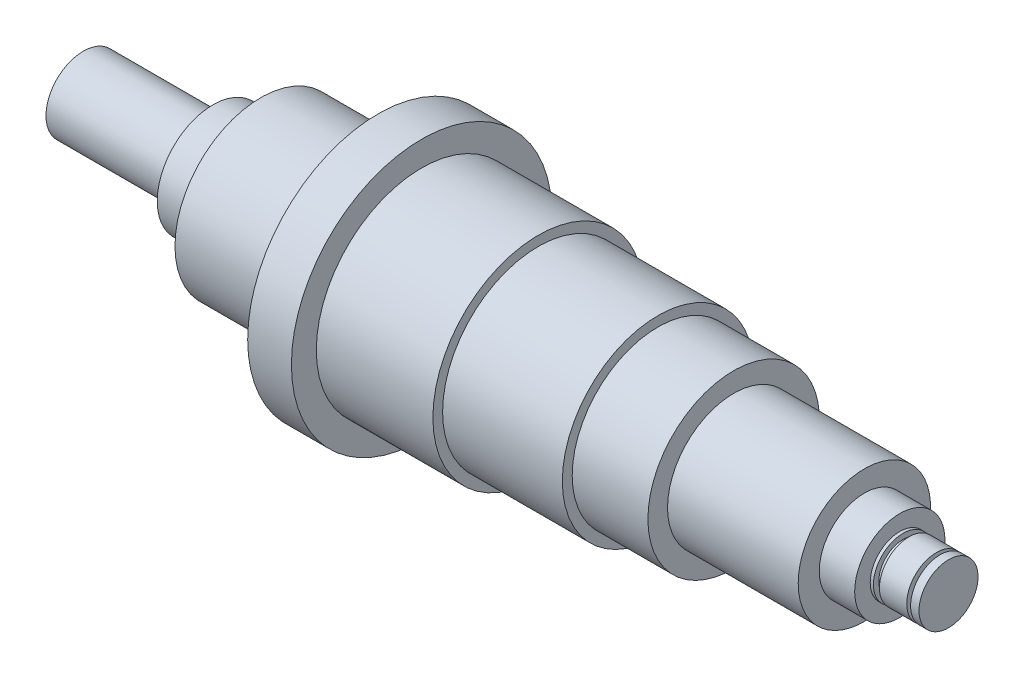
SolidWorks part; units mm, degrees
ref_plane "Front Plane" through (0, 0, 0) normal (0, 0, 1) x (1, 0, 0)
ref_plane "Top Plane" through (0, 0, 0) normal (0, 1, 0) x (1, 0, 0)
ref_plane "Right Plane" through (0, 0, 0) normal (1, 0, 0) x (0, 0, -1)
sketch "Sketch1" plane through (0, 0, 0) normal (0, 0, 1) x (1, 0, 0)
  line L0 (0, 0) -> (0, 25)
  line L1 (0, 25) -> (-7.1483, 25)
  line L2 (-7.1483, 25) -> (-7.1483, 20.4717)
  line L3 (-7.1483, 20.4717) -> (-10.385, 20.4717)
  line L4 (-10.385, 20.4717) -> (-10.385, 25)
  line L5 (-10.385, 25) -> (-33.5041, 25)
  line L6 (-33.5041, 25) -> (-33.5041, 20.4717)
  line L7 (-33.5041, 20.4717) -> (-38.5903, 20.4717)
  line L8 (-38.5903, 20.4717) -> (-38.5903, 25)
  line L9 (-38.5903, 25) -> (-41.311, 25)
  line L10 (-41.311, 25) -> (-41.311, 38.1848)
  line L11 (-41.311, 38.1848) -> (-71.265, 38.1848)
  line L12 (-71.265, 38.1848) -> (-71.265, 56.0242)
  line L13 (-71.265, 56.0242) -> (-181.9301, 56.0242)
  line L14 (-181.9301, 56.0242) -> (-181.9301, 72.6542)
  line L15 (-181.9301, 72.6542) -> (-246.0311, 72.6542)
  line L16 (-246.0311, 72.6542) -> (-246.0311, 81.0107)
  line L17 (-246.0311, 81.0107) -> (-347.4174, 81.0107)
  line L18 (-347.4174, 81.0107) -> (-347.4174, 89.2375)
  line L19 (-347.4174, 89.2375) -> (-446.1389, 89.2375)
  line L20 (-446.1389, 89.2375) -> (-446.1389, 110.3187)
  line L21 (-446.1389, 110.3187) -> (-483.1595, 110.3187)
  line L22 (-483.1595, 110.3187) -> (-483.1595, 72.6542)
  line L23 (-483.1595, 72.6542) -> (-582.3951, 72.6542)
  line L24 (-582.3951, 72.6542) -> (-582.3951, 47.1045)
  line L25 (-582.3951, 47.1045) -> (-622.9323, 47.1045)
  line L26 (-622.9323, 47.1045) -> (-622.9323, 31.5924)
  line L27 (-622.9323, 31.5924) -> (-732.6666, 31.5924)
  line L28 (-732.6666, 0) -> (0, 0)
  line L29 (0, 25) -> (-7.1483, 25)
  line L30 (-732.6666, 31.5924) -> (-732.6666, 0)
revolve "Revolve12" add sketch "Sketch1" angle 360 about L28
